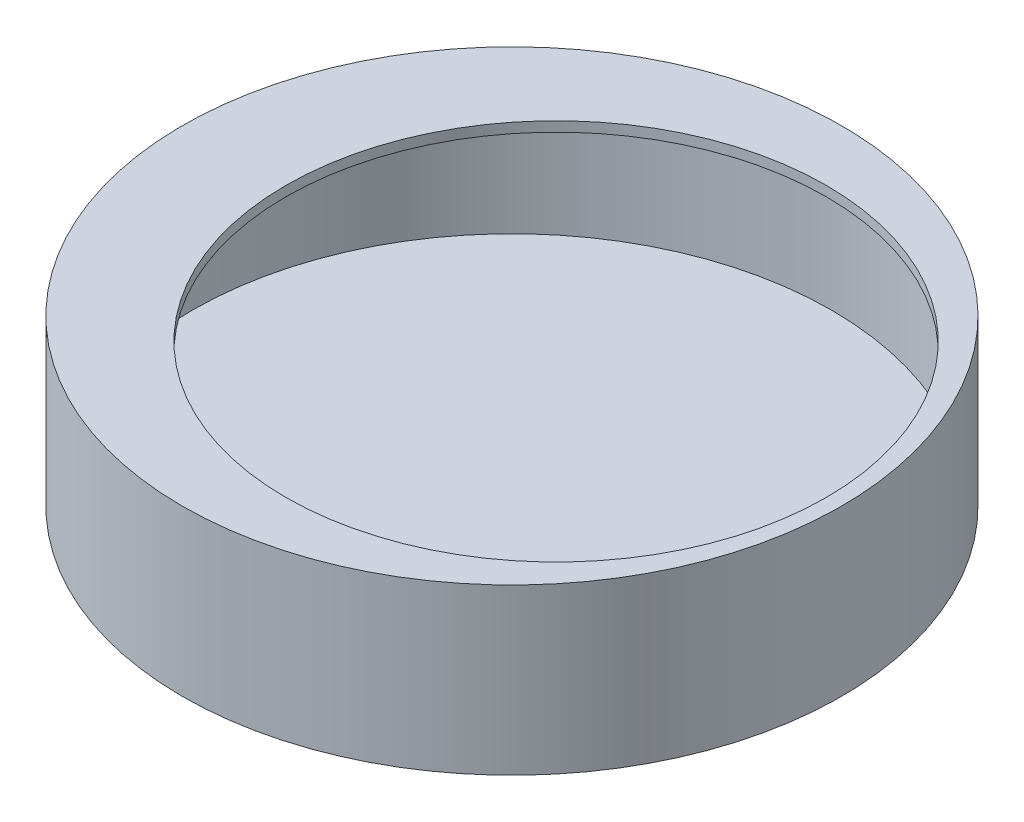
SolidWorks part; units mm, degrees
ref_plane "前视基准面" through (0, 0, 0) normal (0, 0, 1) x (1, 0, 0)
ref_plane "上视基准面" through (0, 0, 0) normal (0, 1, 0) x (1, 0, 0)
ref_plane "右视基准面" through (0, 0, 0) normal (1, 0, 0) x (0, 0, -1)
sketch "草图2" plane through (0, 0, 0) normal (0, 0, 1) x (1, 0, 0)
  line L0 (0, 38.4191) -> (0, -54.6073) construction
  line L1 (0, 5.7237) -> (50, 5.7237)
  line L2 (50, 5.7237) -> (50, -19.2763)
  line L3 (50, -19.2763) -> (0, -19.2763)
  dimension "D1" = 25
  dimension "D2" = 50
revolve "旋转-薄壁6" add sketch "草图2" angle 360 about L0
sketch "草图3" plane through (0, 0, 0) normal (0, 1, 0) x (1, 0, 0)
  line L0 (-54.6414, 0) -> (59.7389, 0) construction
  circle A0 centre (6.6989, 0) radius 41
  dimension "D1" = 82
extrude "切除-拉伸2" cut sketch "草图3" against normal mid plane 12
